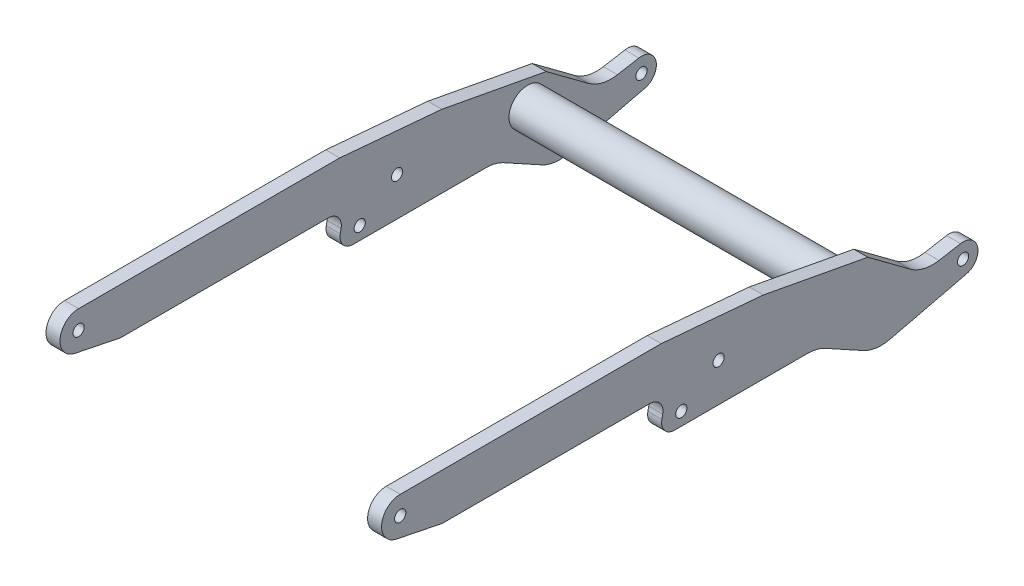
SolidWorks part; units mm, degrees
ref_plane "Front Plane" through (0, 0, 0) normal (0, 0, 1) x (1, 0, 0)
ref_plane "Top Plane" through (0, 0, 0) normal (0, 1, 0) x (1, 0, 0)
ref_plane "Right Plane" through (0, 0, 0) normal (1, 0, 0) x (0, 0, -1)
sketch "Sketch1" plane through (0, 0, 0) normal (1, 0, 0) x (0, 0, -1)
  line L51 (-203.4269, 51.9858) -> (-25.6269, 51.9858)
  line L52 (-25.6269, 51.9858) -> (43.9573, 45.898)
  line L53 (43.9573, 45.898) -> (115.112, 32.5818)
  line L54 (115.112, 32.5818) -> (144.0537, 11.0877)
  line L59 (-25.2063, 7.0304) -> (-24.636, 9.8244)
  line L60 (-33.3464, 20.4924) -> (-174.8584, 20.4924)
  line L61 (-174.8584, 20.4924) -> (-205.9669, 26.8424)
  line L63 (112.0164, -20.9311) -> (86.2818, -6.7804)
  line L64 (74.0433, -3.6376) -> (-16.4959, -3.6376)
  line L65 (163.6098, 6.4654) -> (178.2363, 9.0453)
  line L67 (182.3735, -10.8394) -> (130.1858, -23.3718)
  arc A0 (-203.4269, 51.9858) -> (-205.9669, 26.8424) centre (-203.4269, 39.2858) ccw
  arc A2 (178.2363, 9.0453) -> (182.3735, -10.8394) centre (180.0011, -0.9603) cw
  arc A4 (-16.4959, -3.6376) -> (-25.2063, 7.0304) centre (-16.4959, 5.2524) cw
  arc A5 (-24.636, 9.8244) -> (-33.3464, 20.4924) centre (-33.3464, 11.6024) ccw
  arc A6 (144.0537, 11.0877) -> (163.6098, 6.4654) centre (159.1978, 31.4793) ccw
  arc A7 (130.1858, -23.3718) -> (112.0164, -20.9311) centre (124.2549, 1.3261) cw
  arc A8 (86.2818, -6.7804) -> (74.0433, -3.6376) centre (74.0433, -29.0376) ccw
  circle A9 centre (-203.4269, 39.2858) radius 3.81
  circle A10 centre (-11.936, 5.2524) radius 3.81
  circle A11 centre (13.464, 22.6514) radius 3.81
  circle A12 centre (180.0011, -0.9603) radius 3.81
  point P17 (-27.3839, -3.6376)
  point P20 (-22.4584, 20.4924)
  point P23 (152.8363, 4.5652)
  point P26 (120.6289, -25.6668)
  point P29 (80.5661, -3.6376)
  dimension "D16" = 25.4
  dimension "D5" = 6.35
  dimension "D6" = 31.75
  dimension "D15" = 152.4
  dimension "D17" = 12.7
  dimension "D18" = 24.13
  dimension "D13" = 10.16
  dimension "D19" = 8.89
  dimension "D20" = 25.4
  dimension "D21" = 7.62
  dimension "D2" = 175
  dimension "D3" = 174.4
  dimension "D4" = 154
  dimension "D7" = 177.8
  dimension "D8" = 69.85
  dimension "D9" = 72.39
  dimension "D10" = 46.99
  dimension "D11" = 107.95
  dimension "D12" = 45.72
  dimension "D14" = 63.5
  dimension "D22" = 8.89
  dimension "D23" = 12.7
  dimension ".7" = 25.4
  dimension "D24" = 17.399
extrude "Boss-Extrude2" add sketch "Sketch1" against normal blind 228.6
sketch "Sketch3" plane through (0, 0, 0) normal (0, 1, 0) x (1, 0, 0)
  line L1 (-219.075, 209.9646) -> (-9.525, 209.9646)
  line L2 (-219.075, 209.9646) -> (-219.075, -247.7269)
  line L3 (-219.075, -247.7269) -> (-9.525, -247.7269)
  line L4 (-9.525, 209.9646) -> (-9.525, -247.7269)
  line L5 (-219.075, 209.9646) -> (-9.525, -247.7269) construction
  line L6 (-219.075, -247.7269) -> (-9.525, 209.9646) construction
  point P0 (-114.3, -18.8811)
  dimension "D1" = 9.525
  dimension "D2" = 9.525
extrude "Cut-Extrude1" cut sketch "Sketch3" along normal through all both and the other way through all
sketch "Sketch4" plane through (-219.075, 0, 0) normal (1, 0, 0) x (0, 0, -1)
  line L0 (115.112, 32.5818) -> (43.9573, 45.898) construction
  circle A0 centre (102.412, 18.1619) radius 12.7
  dimension "D1" = 25.4
  dimension "D2" = 16.51
  dimension "D3" = 12.7
extrude "Boss-Extrude3" add sketch "Sketch4" along normal up to next
scale "Scale1" scale about centroid uniform scaling yes scale factor 2.33
